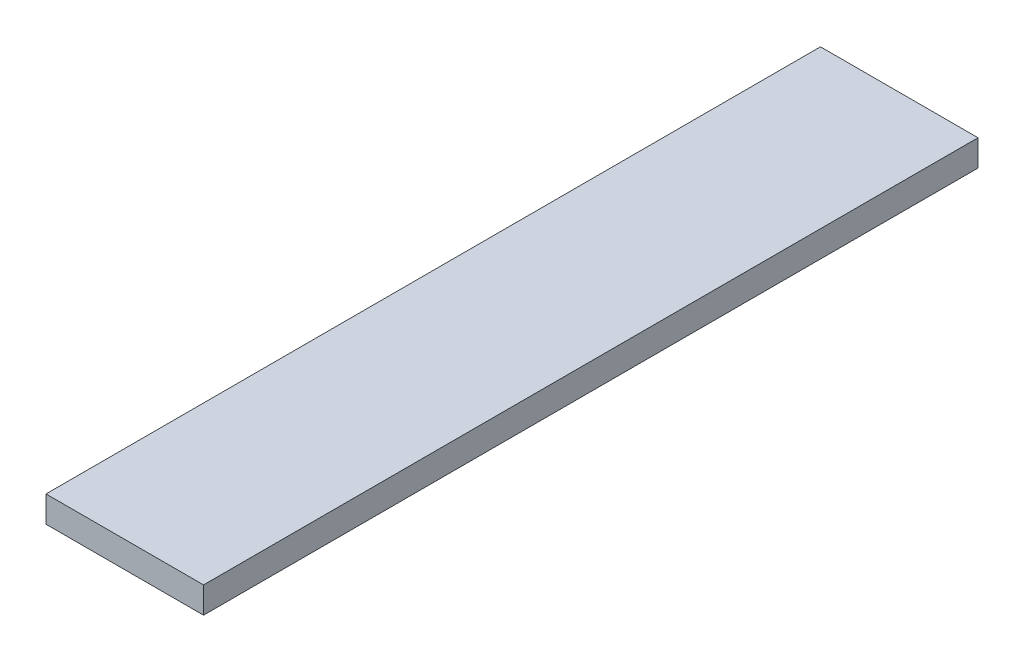
SolidWorks part; units mm, degrees
ref_plane "Front Plane" through (0, 0, 0) normal (0, 0, 1) x (1, 0, 0)
ref_plane "Top Plane" through (0, 0, 0) normal (0, 1, 0) x (1, 0, 0)
ref_plane "Right Plane" through (0, 0, 0) normal (1, 0, 0) x (0, 0, -1)
sketch "Sketch1" plane through (0, 0, 0) normal (0, 0, 1) x (1, 0, 0)
  line L1 (-9.525, -1.5875) -> (9.525, -1.5875)
  line L2 (-9.525, -1.5875) -> (-9.525, 1.5875)
  line L3 (-9.525, 1.5875) -> (9.525, 1.5875)
  line L4 (9.525, -1.5875) -> (9.525, 1.5875)
  line L5 (-9.525, -1.5875) -> (9.525, 1.5875) construction
  line L6 (-9.525, 1.5875) -> (9.525, -1.5875) construction
  point P0 (0, 0)
  dimension "D1" = 3.175
  dimension "D2" = 19.05
extrude "Boss-Extrude1" add sketch "Sketch1" along normal blind 93.65
